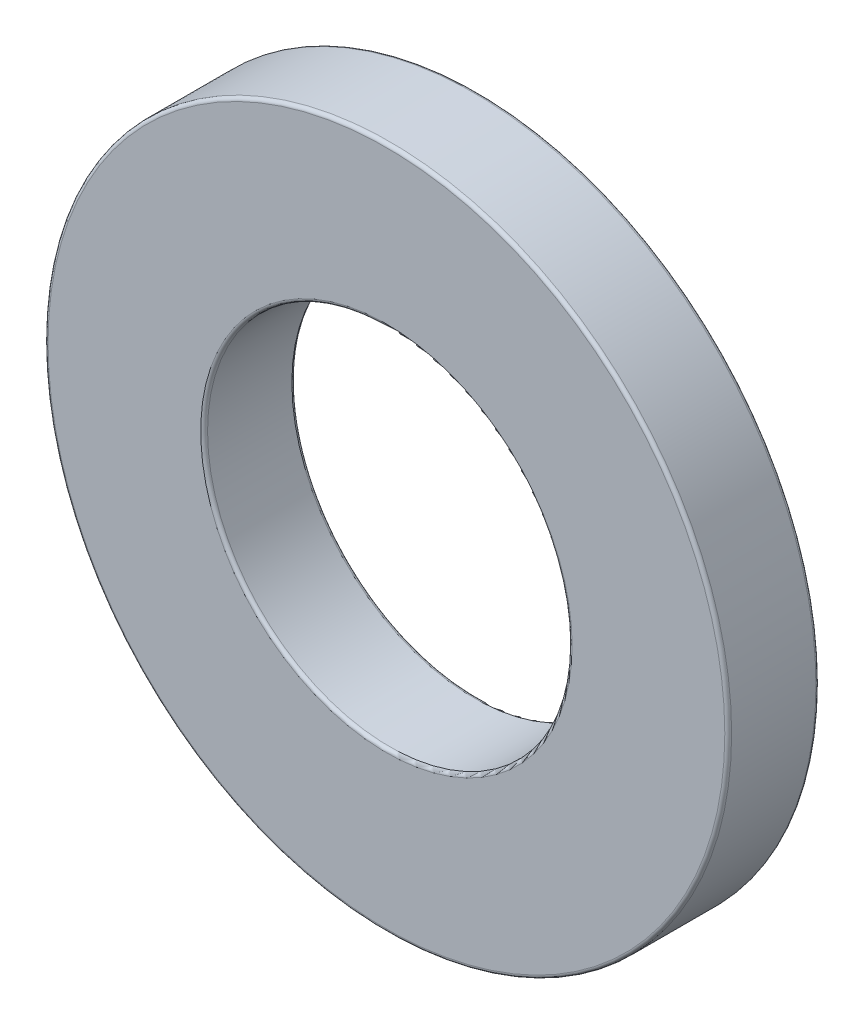
SolidWorks part; units mm, degrees
ref_plane "Front Plane" through (0, 0, 0) normal (0, 0, 1) x (1, 0, 0)
ref_plane "Top Plane" through (0, 0, 0) normal (0, 1, 0) x (1, 0, 0)
ref_plane "Right Plane" through (0, 0, 0) normal (1, 0, 0) x (0, 0, -1)
sketch "Sketch1" plane through (0, 0, 0) normal (0, 0, 1) x (1, 0, 0)
  line L0 (0, 0) -> (3.2, 0) construction
  line L1 (0, -0.165) -> (0, 0.165) construction
  circle A0 centre (0, 0) radius 6
  circle A1 centre (0, 0) radius 3.2
  dimension "D1" = 90
  dimension "OD" = 12
  dimension "ID" = 6.4
sketch "Sketch2" plane through (0, 0, 0) normal (1, 0, 0) x (0, 0, -1)
  line L0 (-0.8, 6) -> (0.8, 6) construction
  point P5 (0, 6)
  dimension "Thickness" = 1.6
sketch "Sketch3" plane through (0, 0, 0) normal (0, 0, 1) x (1, 0, 0)
  circle A0 centre (0, 0) radius 3.2 construction
  circle A1 centre (0, 0) radius 6 construction
  circle A2 centre (0, 0) radius 3.2
  circle A3 centre (0, 0) radius 6
extrude "Boss-Extrude1" add sketch "Sketch3" against normal up to vertex (0.8 mm away) from vertex at 0.8 starting at point (0, 6, 0.8)
fillet "Fillet1" radius 0.06 4 edges at (6, 0, 0.8) (3.2, 0, 0.8) (6, 0, -0.8) (3.2, 0, -0.8)
